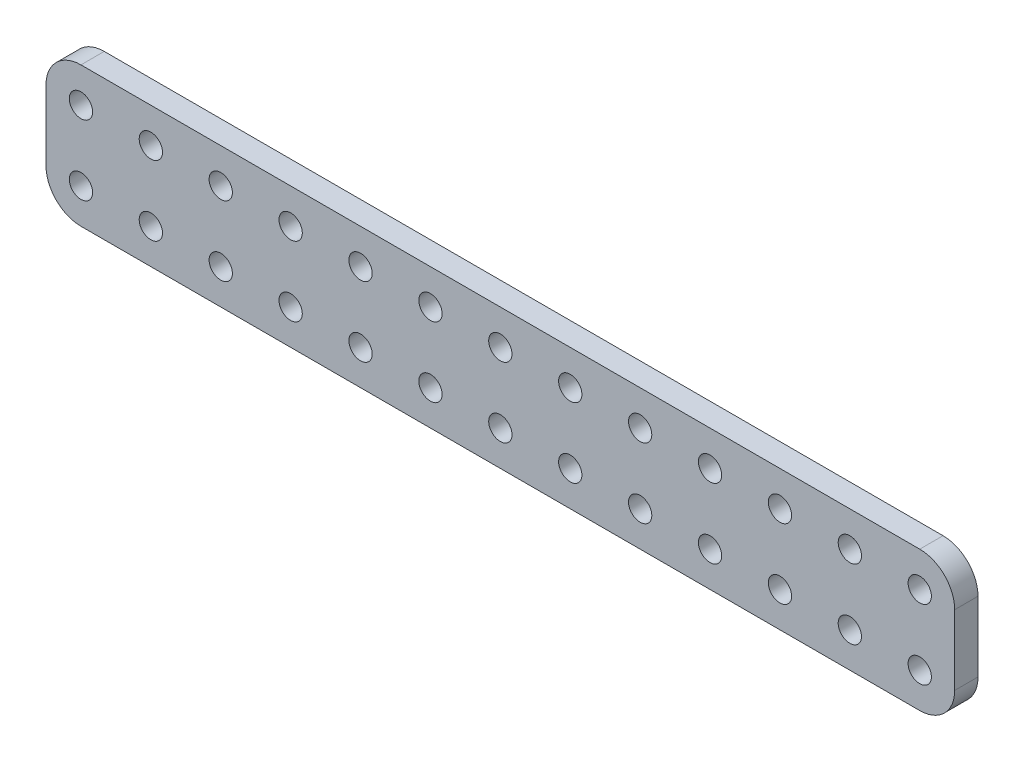
SolidWorks part; units mm, degrees
ref_plane "Alzado" through (0, 0, 0) normal (0, 0, 1) x (1, 0, 0)
ref_plane "Planta" through (0, 0, 0) normal (0, 1, 0) x (1, 0, 0)
ref_plane "Vista lateral" through (0, 0, 0) normal (1, 0, 0) x (0, 0, -1)
sketch "Model" plane through (0, 0, 0) normal (0, 0, 1) x (1, 0, 0)
  line L0 (256.4291, 228.7422) -> (364.4291, 228.7422)
  line L1 (364.4291, 210.7422) -> (256.4291, 210.7422)
  line L2 (368.9291, 224.2422) -> (368.9291, 215.2422)
  line L3 (251.9291, 224.2422) -> (251.9291, 215.2422)
  arc A0 (368.9291, 224.2422) -> (364.4291, 228.7422) centre (364.4291, 224.2422) ccw
  arc A1 (256.4291, 228.7422) -> (251.9291, 224.2422) centre (256.4291, 224.2422) ccw
  arc A2 (251.9291, 215.2422) -> (256.4291, 210.7422) centre (256.4291, 215.2422) ccw
  arc A3 (364.4291, 210.7422) -> (368.9291, 215.2422) centre (364.4291, 215.2422) ccw
  circle A4 centre (310.4291, 224.2422) radius 1.5
  circle A5 centre (292.4291, 224.2422) radius 1.5
  circle A6 centre (301.4291, 224.2422) radius 1.5
  circle A7 centre (337.4291, 215.2422) radius 1.5
  circle A8 centre (319.4291, 215.2422) radius 1.5
  circle A9 centre (328.4291, 215.2422) radius 1.5
  circle A10 centre (310.4291, 215.2422) radius 1.5
  circle A11 centre (292.4291, 215.2422) radius 1.5
  circle A12 centre (301.4291, 215.2422) radius 1.5
  circle A13 centre (274.4291, 215.2422) radius 1.5
  circle A14 centre (283.4291, 215.2422) radius 1.5
  circle A15 centre (265.4291, 215.2422) radius 1.5
  circle A16 centre (256.4291, 215.2422) radius 1.5
  circle A17 centre (346.4291, 215.2422) radius 1.5
  circle A18 centre (274.4291, 224.2422) radius 1.5
  circle A19 centre (265.4291, 224.2422) radius 1.5
  circle A20 centre (256.4291, 224.2422) radius 1.5
  circle A21 centre (283.4291, 224.2422) radius 1.5
  circle A22 centre (337.4291, 224.2422) radius 1.5
  circle A23 centre (319.4291, 224.2422) radius 1.5
  circle A24 centre (328.4291, 224.2422) radius 1.5
  circle A25 centre (346.4291, 224.2422) radius 1.5
  circle A26 centre (355.4291, 215.2422) radius 1.5
  circle A27 centre (355.4291, 224.2422) radius 1.5
  circle A28 centre (364.4291, 215.2422) radius 1.5
  circle A29 centre (364.4291, 224.2422) radius 1.5
extrude "Saliente-Extruir1" add sketch "Model" along normal blind 3
